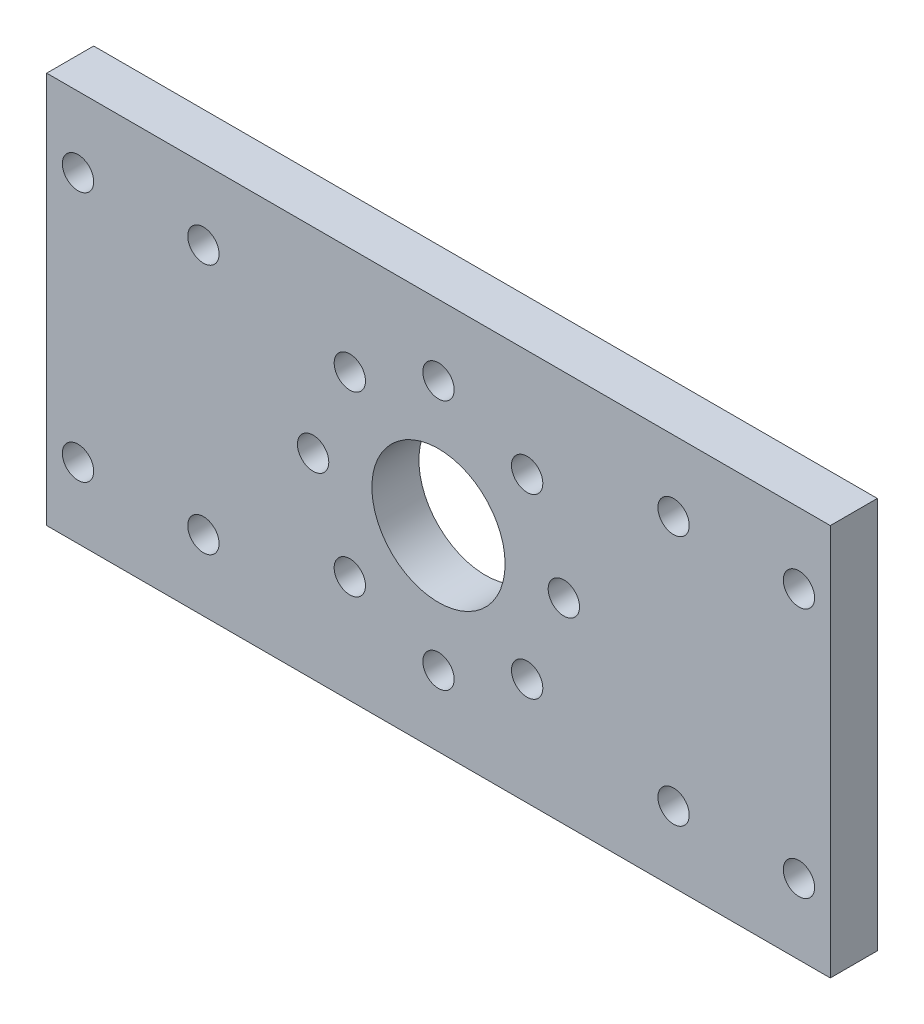
SolidWorks part; units mm, degrees
ref_plane "Plano frontal" through (0, 0, 0) normal (0, 0, 1) x (1, 0, 0)
ref_plane "Plano superior" through (0, 0, 0) normal (0, 1, 0) x (1, 0, 0)
ref_plane "Plano direito" through (0, 0, 0) normal (1, 0, 0) x (0, 0, -1)
sketch "Esboço1" plane through (0, 0, 0) normal (0, 0, 1) x (1, 0, 0)
  line L0 (-15, 8) -> (-15, -8) construction
  line L1 (-25, 12.5) -> (25, 12.5)
  line L2 (-25, 12.5) -> (-25, -12.5)
  line L3 (-25, -12.5) -> (25, -12.5)
  line L4 (25, 12.5) -> (25, -12.5)
  line L5 (-25, 12.5) -> (25, -12.5) construction
  line L6 (-25, -12.5) -> (25, 12.5) construction
  line L7 (0, 12.5) -> (0, -12.5) construction
  circle A0 centre (0, 0) radius 4.25
  circle A1 centre (0, 8) radius 1
  circle A2 centre (5.6569, 5.6569) radius 1
  circle A3 centre (8, 0) radius 1
  circle A4 centre (5.6569, -5.6569) radius 1
  circle A5 centre (0, -8) radius 1
  circle A6 centre (-5.6569, -5.6569) radius 1
  circle A7 centre (-8, 0) radius 1
  circle A8 centre (-5.6569, 5.6569) radius 1
  circle A9 centre (-15, 8) radius 1
  circle A10 centre (-15, -8) radius 1
  circle A11 centre (15, -8) radius 1
  circle A12 centre (15, 8) radius 1
  circle A13 centre (23, 8) radius 1
  circle A14 centre (23, -8) radius 1
  circle A15 centre (-23, -8) radius 1
  circle A16 centre (-23, 8) radius 1
  point P0 (0, 0)
  point P27 (0, 0)
  dimension "D3" = 8.5
  dimension "D4" = 2
  dimension "D5" = 8
  dimension "D7" = 7
  dimension "D8" = 8
  dimension "D1" = 25
  dimension "D2" = 50
  dimension "D6" = 8
extrude "Ressalto-extrusão1" add sketch "Esboço1" along normal blind 3
